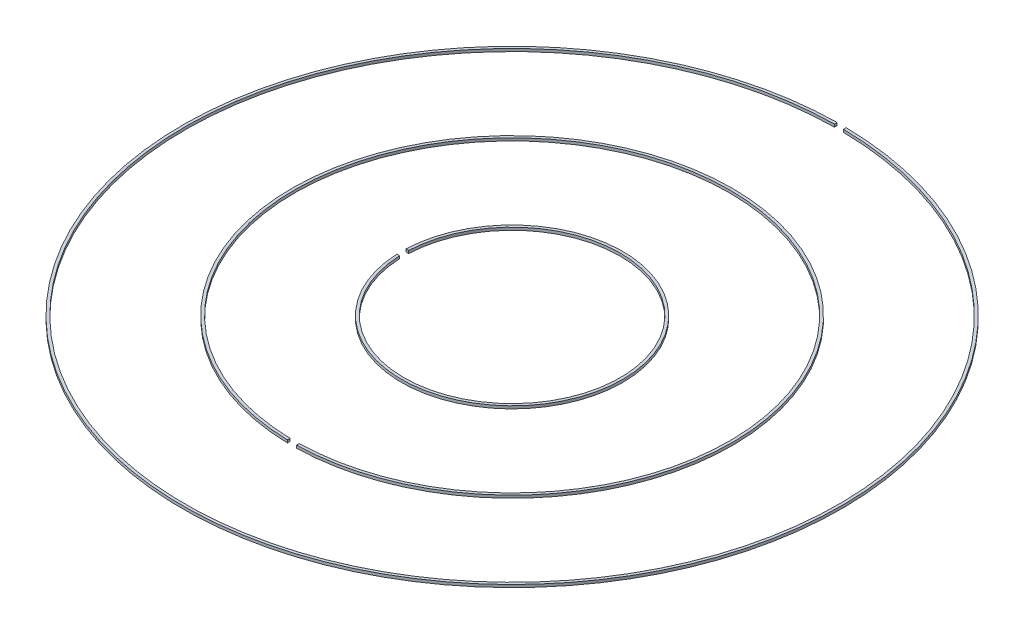
SolidWorks part; units mm, degrees
ref_plane "Front Plane" through (0, 0, 0) normal (0, 0, 1) x (1, 0, 0)
ref_plane "Top Plane" through (0, 0, 0) normal (0, 1, 0) x (1, 0, 0)
ref_plane "Right Plane" through (0, 0, 0) normal (1, 0, 0) x (0, 0, -1)
sketch "Sketch1" plane through (0, 0, 0) normal (0, 1, 0) x (1, 0, 0)
  line L0 (0.06, 4.3826) -> (0.06, 4.3466)
  line L1 (5, 5) -> (-5, 5)
  line L2 (5, 5) -> (5, -5)
  line L3 (5, -5) -> (-5, -5)
  line L4 (-5, 5) -> (-5, -5)
  line L5 (5, 5) -> (-5, -5) construction
  line L6 (5, -5) -> (-5, 5) construction
  line L7 (-0.06, 4.3826) -> (-0.06, 4.3466)
  line L8 (0.06, -2.8914) -> (0.06, -2.9274)
  line L9 (-0.06, -2.8914) -> (-0.06, -2.9274)
  line L10 (-1.4718, 0.06) -> (-1.4358, 0.06)
  line L11 (-1.4358, -0.06) -> (-1.4718, -0.06)
  arc A0 (-0.06, 4.3826) -> (0.06, 4.3826) centre (0, 0) ccw
  arc A1 (-0.06, 4.3466) -> (0.06, 4.3466) centre (0, 0) ccw
  arc A2 (0.06, -2.9274) -> (-0.06, -2.9274) centre (0, 0) ccw
  arc A3 (0.06, -2.8914) -> (-0.06, -2.8914) centre (0, 0) ccw
  arc A4 (-1.4718, -0.06) -> (-1.4718, 0.06) centre (0, 0) ccw
  arc A5 (-1.4358, -0.06) -> (-1.4358, 0.06) centre (0, 0) ccw
  circle A6 centre (0, 0) radius 4.365
  circle A7 centre (0, 0) radius 2.91
  circle A8 centre (0, 0) radius 1.455
  point P0 (0, 0)
  point P8 (-0.06, 4.3646)
  point P22 (0.06, -2.9094)
  point P24 (-1.4538, 0.06)
  point P25 (-1.1703, -0.2271)
  point P26 (-1.4314, -0.1273)
  point P27 (0.06, -2.9274)
  dimension "D2" = 8.73
  dimension "D3" = 5.82
  dimension "D4" = 2.91
  dimension "D5" = 0.036
  dimension "D1" = 10
  dimension "D6" = 0.12
  dimension "D7" = 0.12
extrude "Boss-Extrude1" add sketch "Sketch1" along normal blind 0.036 contours A0 L0 A1 L7 | A2 L9 A3 L8 | A4 L10 A5 L11
